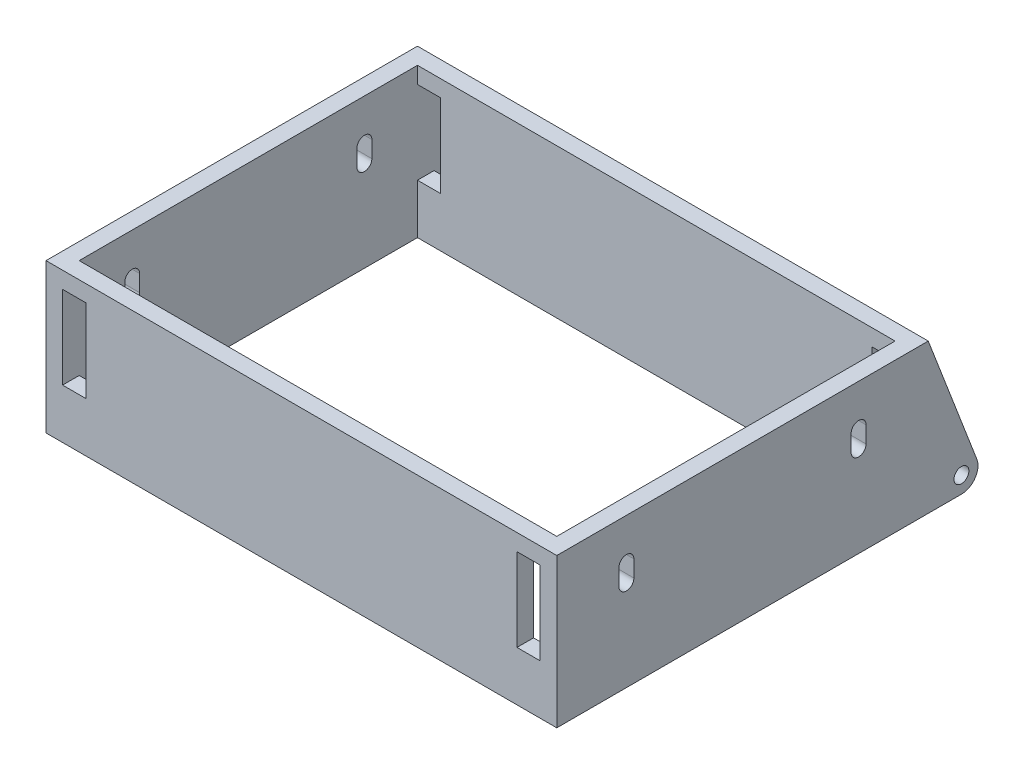
SolidWorks part; units mm, degrees
ref_plane "Front Plane" through (0, 0, 0) normal (0, 0, 1) x (1, 0, 0)
ref_plane "Top Plane" through (0, 0, 0) normal (0, 1, 0) x (1, 0, 0)
ref_plane "Right Plane" through (0, 0, 0) normal (1, 0, 0) x (0, 0, -1)
sketch "Sketch1" plane through (0, 0, 0) normal (0, 1, 0) x (1, 0, 0)
  line L0 (-77, -56) -> (77, -56)
  line L1 (-72, 51) -> (72, 51)
  line L2 (-72, 51) -> (-72, -51)
  line L3 (-72, -51) -> (72, -51)
  line L4 (72, 51) -> (72, -51)
  line L5 (-72, 51) -> (72, -51) construction
  line L6 (-72, -51) -> (72, 51) construction
  line L7 (77, 56) -> (77, -56)
  line L8 (-77, 56) -> (77, 56)
  line L9 (-77, 56) -> (-77, -56)
  line L11 (66, -50) -> (-66, -50)
  line L12 (66, -50) -> (66, 50)
  line L13 (66, 50) -> (-66, 50)
  line L14 (-66, -50) -> (-66, 50)
  line L15 (66, -50) -> (-66, 50) construction
  line L16 (66, 50) -> (-66, -50) construction
  line L17 (-66, 50) -> (-71, 50)
  line L18 (-66, 50) -> (-66, -50)
  line L19 (-66, -50) -> (-71, -50)
  line L20 (-71, 50) -> (-71, -50)
  line L21 (66, -50) -> (71, -50)
  line L22 (66, -50) -> (66, 50)
  line L23 (66, 50) -> (71, 50)
  line L24 (71, -50) -> (71, 50)
  point P0 (0, 0)
  point P10 (0, 0)
  dimension "D1" = 5
  dimension "D2" = 102
  dimension "D4" = 5
  dimension "D5" = 1
  dimension "D6" = 132
  dimension "D7" = 1
  dimension "D3" = 5
extrude "Boss-Extrude1" add sketch "Sketch1" along normal blind 45 contours L8 L9 L0 L7 L1 L4 L3 L2
sketch "Sketch2" plane through (-77, 0, 0) normal (-1, 0, 0) x (0, 0, 1)
  line L0 (-56, 0) -> (56, 0) construction
  line L1 (-35, 32.5) -> (-35, 27.5) construction
  line L2 (-32.75, 32.5) -> (-32.75, 27.5)
  line L3 (-37.25, 32.5) -> (-37.25, 27.5)
  line L4 (35, 32.5) -> (35, 27.5) construction
  line L5 (37.25, 32.5) -> (37.25, 27.5)
  line L6 (32.75, 32.5) -> (32.75, 27.5)
  line L8 (-56, 45) -> (56, 45) construction
  arc A2 (-32.75, 32.5) -> (-37.25, 32.5) centre (-35, 32.5) ccw
  arc A3 (-37.25, 27.5) -> (-32.75, 27.5) centre (-35, 27.5) ccw
  arc A4 (37.25, 32.5) -> (32.75, 32.5) centre (35, 32.5) ccw
  arc A5 (32.75, 27.5) -> (37.25, 27.5) centre (35, 27.5) ccw
  point P2 (-35, 30)
  point P6 (0, 0)
  point P10 (35, 30)
  dimension "D3" = 2.25
  dimension "D4" = 2.25
  dimension "D1" = 70
  dimension "D2" = 35
  dimension "D5" = 5
  dimension "D6" = 5
  dimension "D7" = 12.5
  dimension "D8" = 12.5
extrude "Cut-Extrude1" cut sketch "Sketch2" against normal blind 180.5
sketch "Sketch3" plane through (0, 0, -56) normal (0, 0, -1) x (-1, 0, 0)
  line L0 (-77, 45) -> (-77, 0) construction
  line L1 (-65, 15) -> (-72, 15)
  line L2 (-65, 15) -> (-65, 40)
  line L3 (-65, 40) -> (-72, 40)
  line L4 (-72, 15) -> (-72, 40)
  line L5 (77, 45) -> (-77, 45) construction
  line L6 (77, 0) -> (-77, 0) construction
  line L7 (0, 24.75) -> (0, -24.75) construction
  line L8 (65, 15) -> (72, 15)
  line L9 (72, 15) -> (72, 40)
  line L10 (65, 40) -> (72, 40)
  line L11 (65, 15) -> (65, 40)
  dimension "D1" = 5
  dimension "D2" = 7
  dimension "D3" = 5
  dimension "D4" = 15
extrude "Cut-Extrude3" cut sketch "Sketch3" against normal blind 134
sketch "Sketch4" plane through (-77, 0, 0) normal (-1, 0, 0) x (0, 0, 1)
  line L0 (-56, 0) -> (-66, 0)
  line L2 (-56, 45) -> (-56, 0) construction
  line L3 (-56, 45) -> (-70.6679, 6.792)
  circle A0 centre (-66, 5) radius 2.25
  circle A1 centre (-66, 5) radius 5
  dimension "D2" = 4.5
  dimension "D4" = 10
  dimension "D1" = 10
  dimension "D3" = 5
  dimension "D5" = 10
extrude "Boss-Extrude2" add sketch "Sketch4" against normal blind 5
pattern_linear "LPattern1" count 2 spacing 12 along (1, 0, 0) of "Boss-Extrude2"
mirror "Mirror1" about plane through (0, 0, 0) normal (1, 0, 0) of "LPattern1", "Boss-Extrude2"
